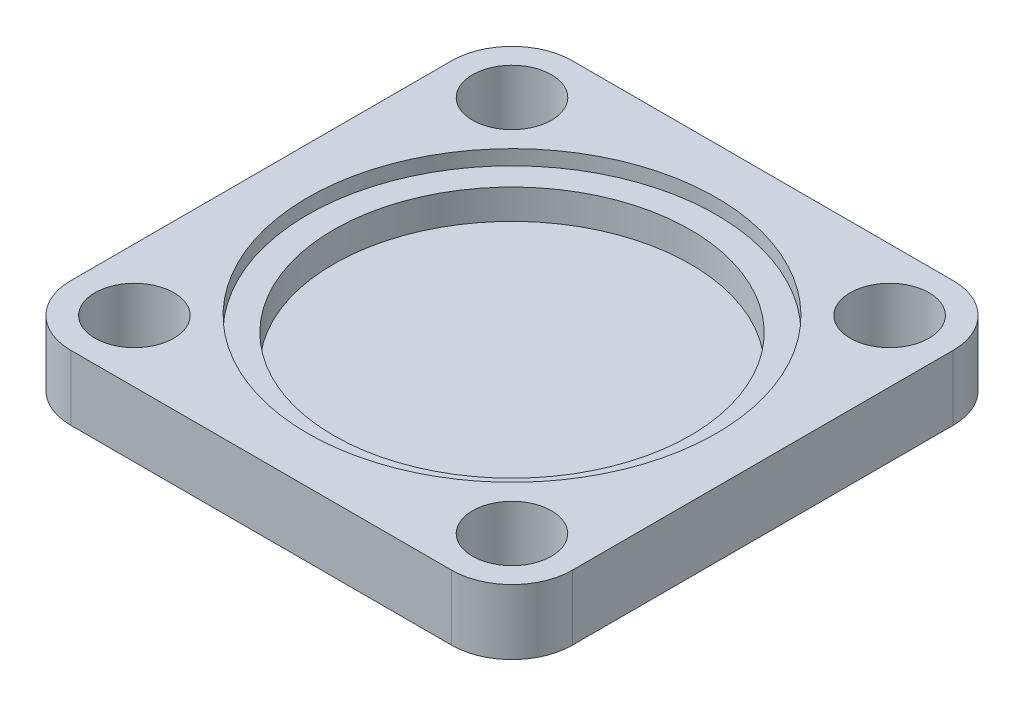
SolidWorks part; units mm, degrees
ref_plane "Front Plane" through (0, 0, 0) normal (0, 0, 1) x (1, 0, 0)
ref_plane "Top Plane" through (0, 0, 0) normal (0, 1, 0) x (1, 0, 0)
ref_plane "Right Plane" through (0, 0, 0) normal (1, 0, 0) x (0, 0, -1)
sketch "Sketch1" plane through (0, 0, 0) normal (0, 1, 0) x (1, 0, 0)
  line L0 (0, 27) -> (0, -27) construction
  line L1 (-27, 27) -> (27, 27)
  line L2 (-27, 27) -> (-27, -27)
  line L3 (-27, -27) -> (27, -27)
  line L4 (27, 27) -> (27, -27)
  line L5 (-27, 27) -> (27, -27) construction
  line L6 (-27, -27) -> (27, 27) construction
  line L7 (-17.3241, 17.3241) -> (17.3241, 17.3241) construction
  line L8 (-17.3241, 17.3241) -> (-17.3241, -17.3241) construction
  line L9 (-17.3241, -17.3241) -> (17.3241, -17.3241) construction
  line L10 (17.3241, 17.3241) -> (17.3241, -17.3241) construction
  line L11 (-17.3241, 17.3241) -> (17.3241, -17.3241) construction
  line L12 (-17.3241, -17.3241) -> (17.3241, 17.3241) construction
  circle A0 centre (-20.3293, 20.3293) radius 4.25
  circle A1 centre (20.3293, -20.3293) radius 4.25
  circle A2 centre (-20.3293, -20.3293) radius 4.25
  circle A3 centre (20.3293, 20.3293) radius 4.25
  point P0 (0, 0)
  point P6 (0, 0)
  dimension "D4" = 8.5
  dimension "D1" = 54
  dimension "D2" = 54
  dimension "D3" = 49
extrude "Boss-Extrude1" add sketch "Sketch1" along normal blind 7
sketch "Sketch2" plane through (0, 7, 0) normal (0, 1, 0) x (1, 0, 0)
  circle A0 centre (0, 0) radius 22
  dimension "D1" = 44
fillet "Fillet2" radius 6.5 4 edges at (-27, 3.5, 27) (27, 3.5, 27) (27, 3.5, -27) (-27, 3.5, -27)
extrude "Cut-Extrude1" cut sketch "Sketch2" against normal blind 1.6
sketch "Sketch3" plane through (0, 5.4, 0) normal (0, 1, 0) x (1, 0, 0)
  circle A0 centre (0, 0) radius 19.2
  dimension "D1" = 38.4
extrude "Cut-Extrude2" cut sketch "Sketch3" against normal blind 3.2
